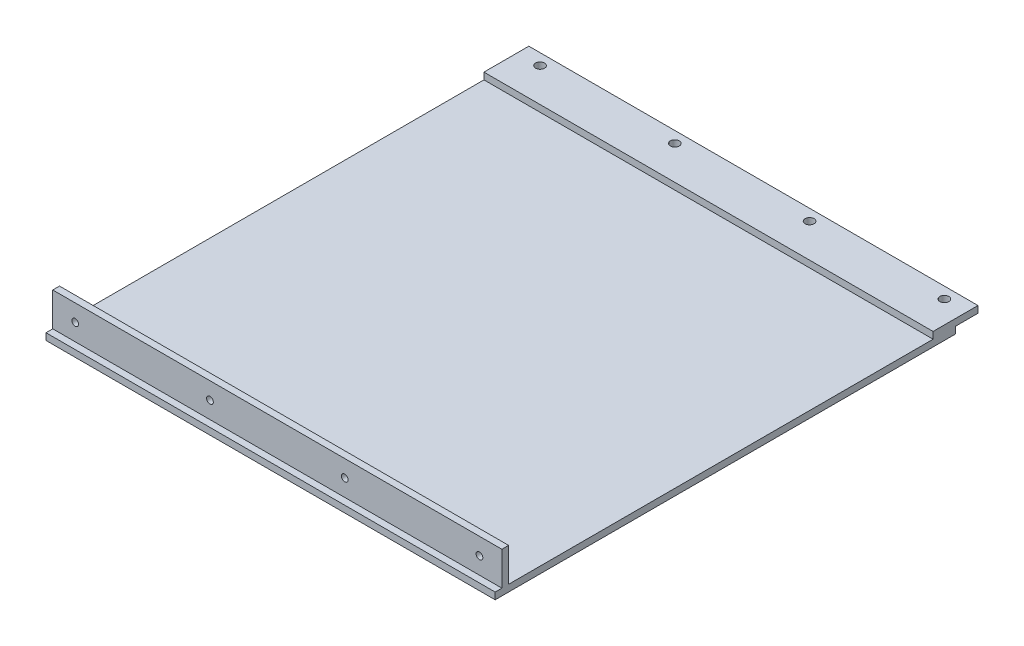
SolidWorks part; units mm, degrees
ref_plane "Front Plane" through (0, 0, 0) normal (0, 0, 1) x (1, 0, 0)
ref_plane "Top Plane" through (0, 0, 0) normal (0, 1, 0) x (1, 0, 0)
ref_plane "Right Plane" through (0, 0, 0) normal (1, 0, 0) x (0, 0, -1)
sketch "Sketch1" plane through (0, 0, 0) normal (0, 1, 0) x (1, 0, 0)
  line L1 (-100, -102.5) -> (100, -102.5)
  line L2 (-100, -102.5) -> (-100, 102.5)
  line L3 (-100, 102.5) -> (100, 102.5)
  line L4 (100, -102.5) -> (100, 102.5)
  line L5 (-100, -102.5) -> (100, 102.5) construction
  line L6 (-100, 102.5) -> (100, -102.5) construction
  point P0 (0, 0)
  dimension "D1" = 205
  dimension "D2" = 200
extrude "Boss-Extrude1" add sketch "Sketch1" along normal blind 3 contours L2 L3 L4 L1
sketch "Sketch2" plane through (0, 3, 0) normal (0, 1, 0) x (1, 0, 0)
  line L0 (-100, -102.5) -> (-100, 102.5) construction
  line L1 (-100, 92.5) -> (100, 92.5)
  line L2 (-100, 92.5) -> (-100, 112.5)
  line L3 (-100, 112.5) -> (100, 112.5)
  line L4 (100, 92.5) -> (100, 112.5)
  line L5 (100, -102.5) -> (100, 102.5) construction
  line L6 (-100, 102.5) -> (100, 102.5) construction
  dimension "D1" = 10
  dimension "D2" = 10
extrude "Boss-Extrude2" add sketch "Sketch2" along normal blind 3
sketch "Sketch3" plane through (0, 6, 0) normal (0, 1, 0) x (1, 0, 0)
  line L0 (100, 112.5) -> (-100, 112.5) construction
  line L1 (-100, 112.5) -> (-100, 92.5) construction
  circle A0 centre (-90, 107.5) radius 2
  dimension "D1" = 4
  dimension "D2" = 5
  dimension "D3" = 10
extrude "Cut-Extrude1" cut sketch "Sketch3" against normal up to next
pattern_linear "LPattern1" count 4 spacing 60 along (1, 0, 0) of "Cut-Extrude1"
sketch "Sketch4" plane through (0, 3, 0) normal (0, 1, 0) x (1, 0, 0)
  line L0 (100, -102.5) -> (100, 92.5) construction
  line L1 (-100, -99.5) -> (100, -99.5)
  line L2 (-100, -99.5) -> (-100, -96.5)
  line L3 (-100, -96.5) -> (100, -96.5)
  line L4 (100, -99.5) -> (100, -96.5)
  line L5 (-100, -102.5) -> (100, -102.5) construction
  line L6 (-100, -102.5) -> (-100, 92.5) construction
  point P9 (-100, -99.5)
  dimension "D1" = 3
  dimension "D2" = 3
extrude "Boss-Extrude3" add sketch "Sketch4" along normal blind 15
sketch "Sketch5" plane through (0, 0, 99.5) normal (0, 0, 1) x (1, 0, 0)
  line L0 (-100, 18) -> (100, 18) construction
  line L1 (-100, 18) -> (-100, 3) construction
  circle A0 centre (-90, 10.5) radius 1.5
  dimension "D2" = 3
  dimension "D1" = 7.5
  dimension "D3" = 10
extrude "Cut-Extrude2" cut sketch "Sketch5" against normal up to next
pattern_linear "LPattern2" count 4 spacing 60 along (1, 0, 0) of "Cut-Extrude2"
